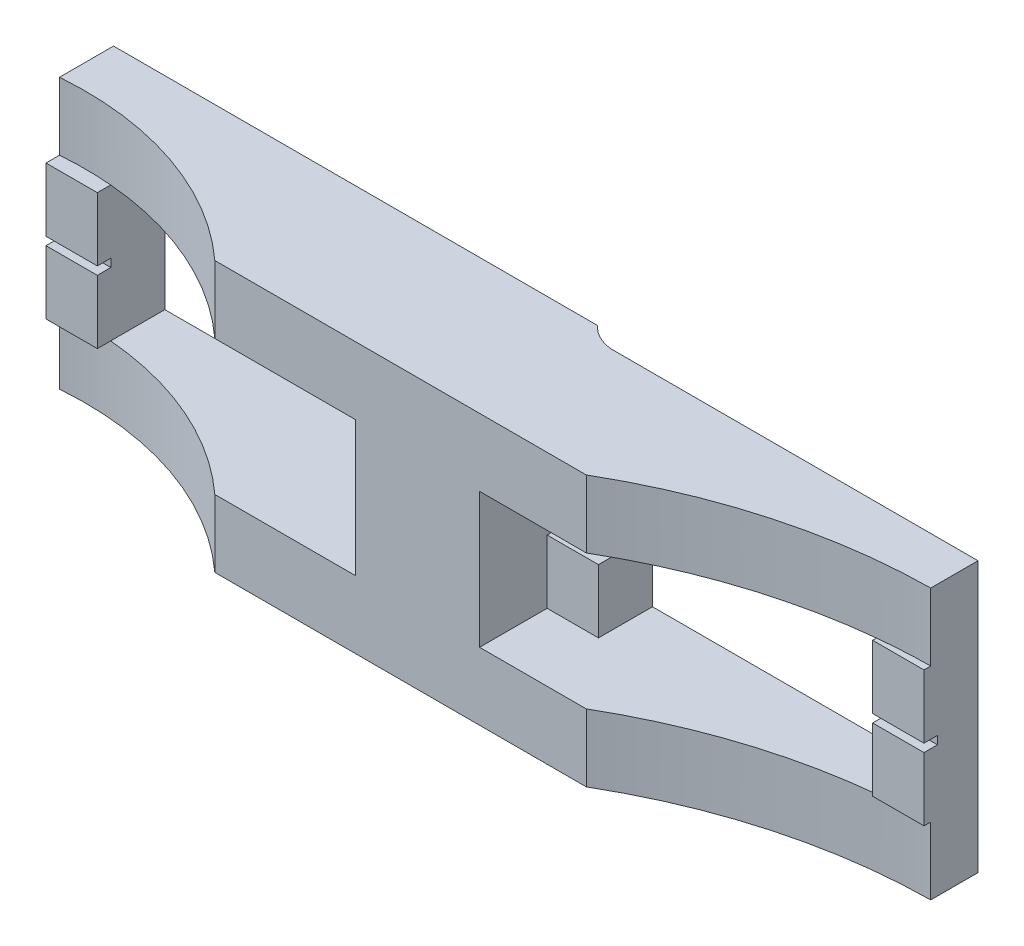
SolidWorks part; units mm, degrees
ref_plane "Front Plane" through (0, 0, 0) normal (0, 0, 1) x (1, 0, 0)
ref_plane "Top Plane" through (0, 0, 0) normal (0, 1, 0) x (1, 0, 0)
ref_plane "Right Plane" through (0, 0, 0) normal (1, 0, 0) x (0, 0, -1)
sketch "Sketch1" plane through (0, 0, 0) normal (0, 1, 0) x (1, 0, 0)
  line L0 (23.978, 8) -> (65, 8)
  line L1 (-20, 10) -> (6.6612, 10)
  line L3 (-20, -10) -> (20, -10)
  line L5 (-20, 10) -> (20, -10) construction
  line L6 (-20, -10) -> (20, 10) construction
  line L7 (65, 8) -> (65, 1)
  line L8 (20, -10) -> (17.8387, -10)
  line L9 (-20, 10) -> (-65, 10)
  line L10 (-65, 10) -> (-65, 2)
  line L11 (20, -10) -> (25, -10)
  line L12 (-20, -10) -> (-30, -10)
  line L13 (23.978, 8) -> (10.7791, 8)
  arc A0 (25, -10) -> (65, 1) centre (65.758, -79.9837) cw
  arc A1 (-65, 2) -> (-30, -10) centre (-61.3476, -44.3888) cw
  arc A5 (10.7791, 8) -> (6.6612, 10) centre (11.1967, 14.099) cw
  point P0 (0, 0)
  point P18 (20, 8)
  dimension "D1" = 20
  dimension "D2" = 40
  dimension "D3" = 45
  dimension "D4" = 45
  dimension "D5" = 2
  dimension "D6" = 7
  dimension "D7" = 5
  dimension "D8" = 8
  dimension "D9" = 10
extrude "Boss-Extrude1" add sketch "Sketch1" along normal blind 40
sketch "Sketch2" plane through (0, 0, 10) normal (0, 0, 1) x (1, 0, 0)
  line L0 (-65, 20) -> (65, 20) construction
  line L1 (-65, 40) -> (-65, 0) construction
  line L2 (65, 40) -> (65, 0) construction
  line L3 (9.2, 30) -> (9.2, 10)
  line L4 (9.2, 30) -> (65, 30)
  line L5 (65, 30) -> (65, 10)
  line L6 (65, 10) -> (9.2, 10)
  line L7 (0, 0) -> (0, 40) construction
  line L8 (25, 40) -> (-30, 40) construction
  line L9 (-9.2, 30) -> (-9.2, 10)
  line L10 (-65, 10) -> (-9.2, 10)
  line L11 (-9.2, 30) -> (-65, 30)
  line L12 (-65, 30) -> (-65, 10)
  point P9 (9.2, 20)
  dimension "D1" = 20
  dimension "D2" = 55.8
extrude "Cut-Extrude1" cut sketch "Sketch2" against normal blind 13.5
sketch "Sketch3" plane through (0, 0, -3.5) normal (0, 0, 1) x (1, 0, 0)
  line L0 (16.8, 30) -> (16.8, 10)
  line L1 (57.4, 30) -> (57.4, 10)
  line L2 (-57.4, 30) -> (-57.4, 10)
  line L3 (-65, 30) -> (-30, 30) construction
  line L4 (9.2, 10) -> (65, 10)
  line L5 (65, 10) -> (65, 30)
  line L6 (65, 30) -> (9.2, 30)
  line L7 (9.2, 30) -> (9.2, 10)
  line L8 (9.2, 10) -> (65, 10)
  line L9 (65, 10) -> (65, 30)
  line L10 (65, 30) -> (9.2, 30)
  line L11 (9.2, 30) -> (9.2, 10)
  line L12 (-65, 10) -> (-9.2, 10) construction
  line L13 (-16.8, 30) -> (-16.8, 10)
  line L14 (-9.2, 30) -> (-65, 30) construction
  line L15 (-30, 10) -> (-9.2, 10) construction
  line L22 (-9.2, 30) -> (-65, 30)
  line L23 (-65, 30) -> (-65, 10)
  line L24 (-65, 10) -> (-9.2, 10)
  line L25 (-9.2, 10) -> (-9.2, 30)
  line L26 (-9.2, 30) -> (-65, 30)
  line L27 (-65, 30) -> (-65, 10)
  line L28 (-65, 10) -> (-9.2, 10)
  line L29 (-9.2, 10) -> (-9.2, 30)
  line M13 (-9.2, 30) -> (-65, 30)
  line M15 (-65, 10) -> (-9.2, 10)
  dimension "D1" = 0
  dimension "D6" = 0
extrude "Cut-Extrude2" cut sketch "Sketch3" against normal up to next contours L13 L2 M13 M15 | L1 L10 L0 L8
sketch "Sketch4" plane through (0, 0, -3.5) normal (0, 0, 1) x (1, 0, 0)
  line L4 (-57.4, 10) -> (-57.4, 30)
  line L5 (-57.4, 30) -> (-65, 30)
  line L6 (-65, 30) -> (-65, 10)
  line L7 (-65, 10) -> (-57.4, 10)
  line L8 (-57.4, 10) -> (-57.4, 30)
  line L9 (-57.4, 30) -> (-65, 30)
  line L10 (-65, 30) -> (-65, 10)
  line L11 (-65, 10) -> (-57.4, 10)
  line L12 (-9.2, 30) -> (-16.8, 30)
  line L13 (-16.8, 30) -> (-16.8, 10)
  line L14 (-16.8, 10) -> (-9.2, 10)
  line L15 (-9.2, 10) -> (-9.2, 30)
  line L16 (-9.2, 30) -> (-16.8, 30)
  line L17 (-16.8, 30) -> (-16.8, 10)
  line L18 (-16.8, 10) -> (-9.2, 10)
  line L19 (-9.2, 10) -> (-9.2, 30)
  line L20 (16.8, 10) -> (16.8, 30)
  line L21 (16.8, 30) -> (9.2, 30)
  line L22 (9.2, 30) -> (9.2, 10)
  line L23 (9.2, 10) -> (16.8, 10)
  line L24 (16.8, 10) -> (16.8, 30)
  line L25 (16.8, 30) -> (9.2, 30)
  line L26 (9.2, 30) -> (9.2, 10)
  line L27 (9.2, 10) -> (16.8, 10)
  line L28 (65, 30) -> (57.4, 30)
  line L29 (57.4, 30) -> (57.4, 10)
  line L30 (57.4, 10) -> (65, 10)
  line L31 (65, 10) -> (65, 30)
  line L32 (65, 30) -> (57.4, 30)
  line L33 (57.4, 30) -> (57.4, 10)
  line L34 (57.4, 10) -> (65, 10)
  line L35 (65, 10) -> (65, 30)
  dimension "D1" = 0
  dimension "D2" = 0
  dimension "D3" = 0
  dimension "D4" = 0
extrude "Boss-Extrude2" add sketch "Sketch4" along normal blind 3.5
sketch "Sketch5" plane through (0, 0, 0) normal (0, 0, 1) x (1, 0, 0)
  line L0 (-65, 20.6) -> (-65, 19.4)
  line L1 (-65, 30) -> (-65, 10) construction
  line L3 (-65, 20.6) -> (-9.2, 20.6)
  line L4 (-9.2, 10) -> (-9.2, 30) construction
  line L5 (-65, 19.4) -> (-9.2, 19.4)
  line L6 (-9.2, 20.6) -> (-9.2, 19.4)
extrude "Cut-Extrude3" cut sketch "Sketch5" against normal blind 2
sketch "Sketch6" plane through (0, 0, 0) normal (0, 0, 1) x (1, 0, 0)
  line L0 (9.2, 20) -> (65, 20) construction
  line L1 (9.2, 30) -> (9.2, 10) construction
  line L2 (65, 10) -> (65, 30) construction
  line L3 (9.2, 20.6) -> (65, 20.6)
  line L4 (9.2, 19.4) -> (65, 19.4)
  line L5 (9.2, 19.4) -> (9.2, 20.6)
  line L6 (65, 19.4) -> (65, 20.6)
  dimension "D1" = 0.6
extrude "Cut-Extrude4" cut sketch "Sketch6" against normal blind 2
